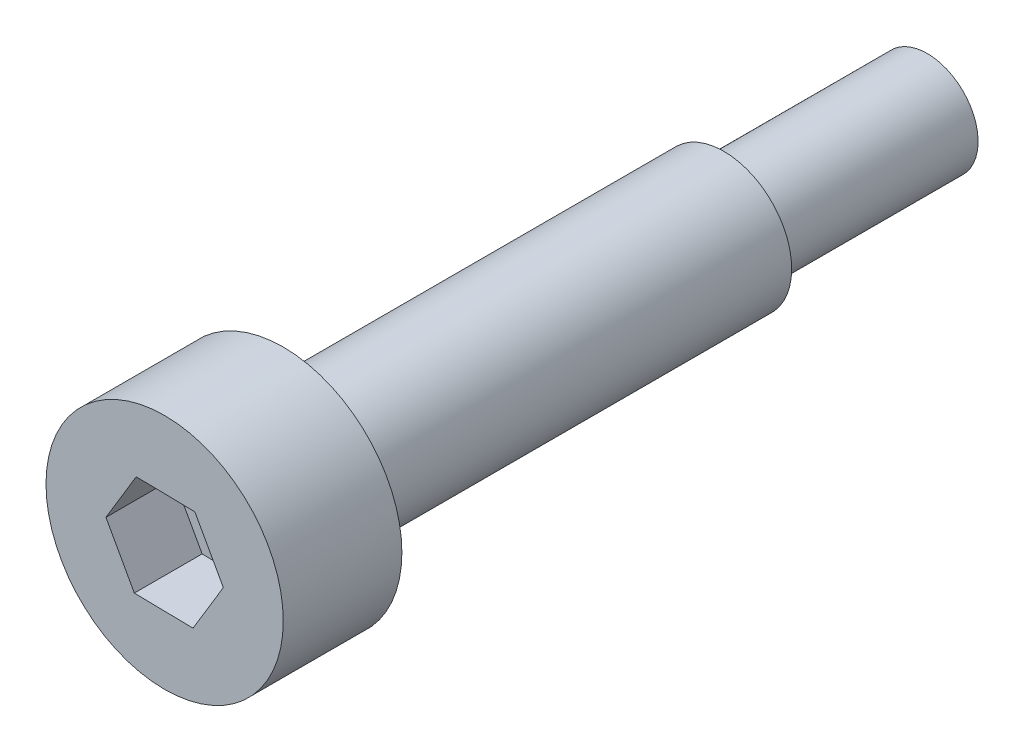
SolidWorks part; units mm, degrees
material "AISI 304"
ref_plane "前视基准面" through (0, 0, 0) normal (0, 0, 1) x (1, 0, 0)
ref_plane "上视基准面" through (0, 0, 0) normal (0, 1, 0) x (1, 0, 0)
ref_plane "右视基准面" through (0, 0, 0) normal (1, 0, 0) x (0, 0, -1)
sketch "草图1" plane through (0, 0, 0) normal (0, 0, 1) x (1, 0, 0)
  circle A0 centre (0, 0) radius 3.5
  dimension "D1" = 7
extrude "凸台-拉伸1" add sketch "草图1" along normal blind 3.5
sketch "草图2" plane through (0, 0, 3.5) normal (0, 0, 1) x (1, 0, 0)
  line L1 (0.8936, 1.4837) -> (-0.8381, 1.5158)
  line L2 (-0.8381, 1.5158) -> (-1.7318, 0.0321)
  line L3 (-1.7318, 0.0321) -> (-0.8936, -1.4837)
  line L4 (-0.8936, -1.4837) -> (0.8381, -1.5158)
  line L5 (0.8381, -1.5158) -> (1.7318, -0.0321)
  line L6 (1.7318, -0.0321) -> (0.8936, 1.4837)
  circle A0 centre (0, 0) radius 1.5 construction
  dimension "D1" = 3
extrude "切除-拉伸1" cut sketch "草图2" against normal blind 2
sketch "草图3" plane through (0, 0, 0) normal (0, 0, -1) x (-1, 0, 0)
  circle A0 centre (0, 0) radius 2
  dimension "D1" = 4
extrude "凸台-拉伸2" add sketch "草图3" along normal blind 13
sketch "草图4" plane through (0, 0, -13) normal (0, 0, -1) x (-1, 0, 0)
  circle A0 centre (0, 0) radius 1.5
  dimension "D1" = 3
extrude "凸台-拉伸3" add sketch "草图4" along normal blind 6
cosmetic thread "装饰螺纹线1" parameters "D2"=2
